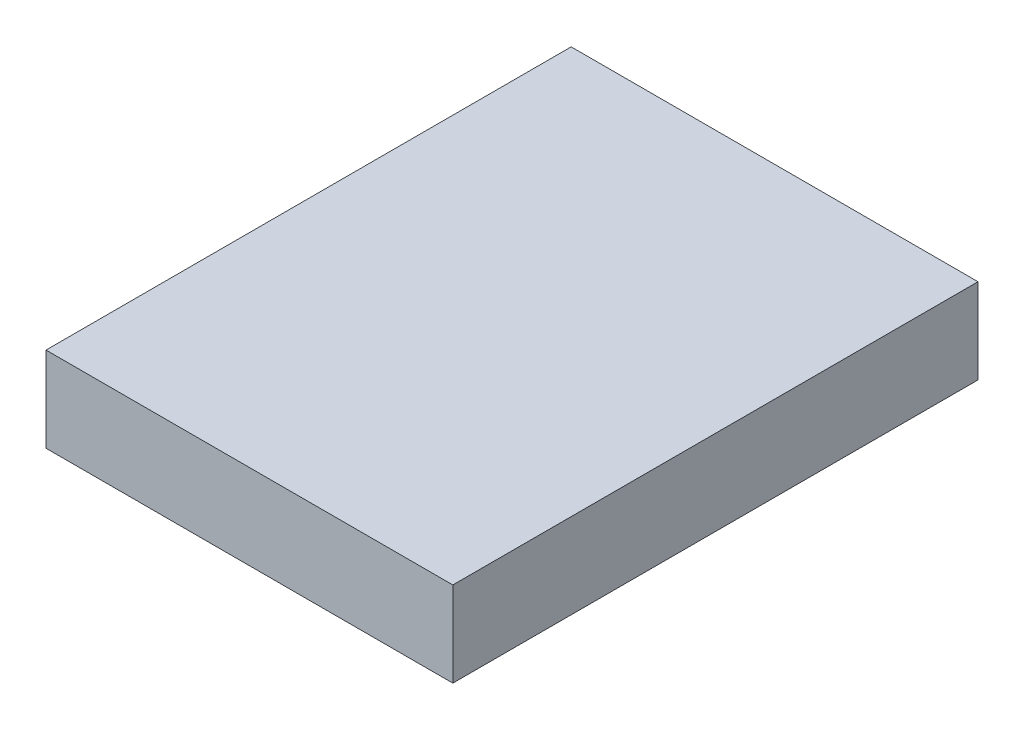
SolidWorks part; units mm, degrees
ref_plane "Front" through (0, 0, 0) normal (0, 0, 1) x (1, 0, 0)
ref_plane "Top" through (0, 0, 0) normal (0, 1, 0) x (1, 0, 0)
ref_plane "Right" through (0, 0, 0) normal (1, 0, 0) x (0, 0, -1)
sketch "Sketch1" plane through (0, 0, 0) normal (0, 1, 0) x (1, 0, 0)
  line L0 (0, 0) -> (0, 71)
  line L1 (0, 71) -> (55, 71)
  line L2 (55, 71) -> (55, 0)
  line L3 (55, 0) -> (0, 0)
extrude "Boss-Extrude1" add sketch "Sketch1" along normal blind 11.5
